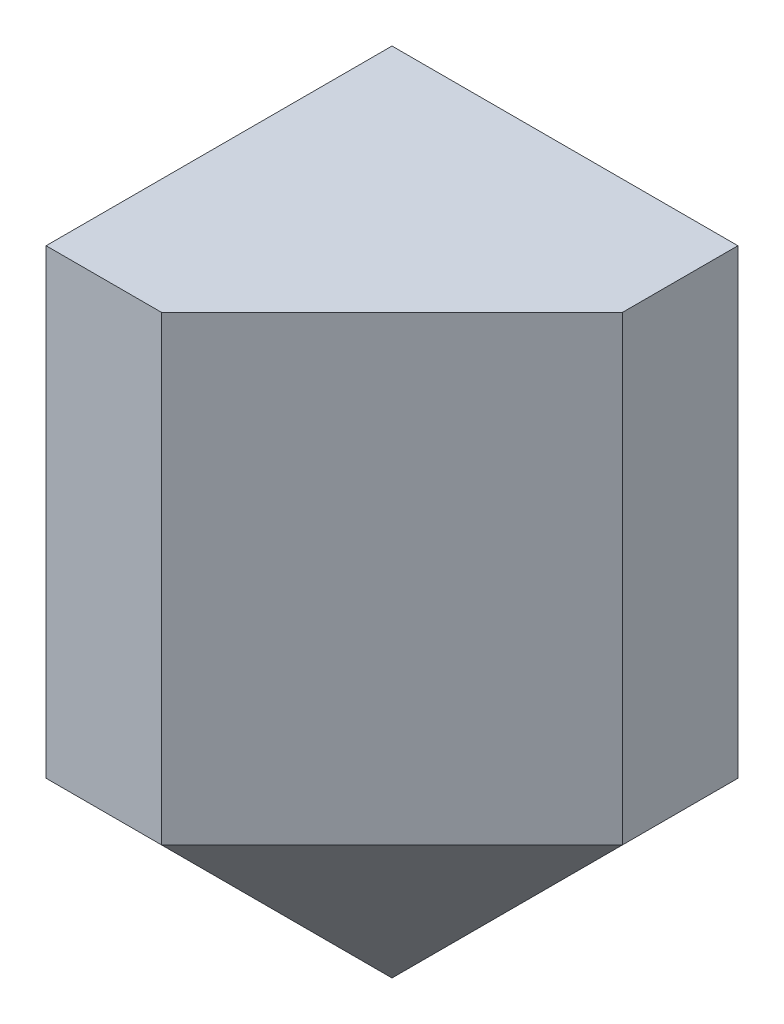
SolidWorks part; units mm, degrees
material "ABS generico"
ref_plane "Piano frontale" through (0, 0, 0) normal (0, 0, 1) x (1, 0, 0)
ref_plane "Piano superiore" through (0, 0, 0) normal (0, 1, 0) x (1, 0, 0)
ref_plane "Piano destro" through (0, 0, 0) normal (1, 0, 0) x (0, 0, -1)
sketch "Schizzo1" plane through (0, 0, 0) normal (0, 0, 1) x (1, 0, 0)
  line L1 (0, 0) -> (30, 0)
  line L2 (0, 0) -> (0, 40)
  line L3 (0, 40) -> (30, 40)
  line L4 (30, 0) -> (30, 40)
  dimension "D1" = 30
  dimension "D2" = 40
extrude "Estrusione-Estrusione1" add sketch "Schizzo1" along normal blind 30
chamfer "Smusso1" distance 20 angle 45 3 edges at (30, 20, 30) (30, 0, 15) (15, 0, 30)
sketch "Schizzo2" plane through (0, 40, 0) normal (0, 1, 0) x (1, 0, 0)
  line L0 (0, 0) -> (30, 0)
  line L1 (30, 0) -> (30, -10)
  line L2 (30, -10) -> (10, -30)
  line L3 (10, -30) -> (0, -30)
  line L4 (0, -30) -> (0, 0)
extrude "Estrusione-Estrusione2" add sketch "Schizzo2" along normal blind 20
hole_wizard "Foro per Vite M5-1" positions "Schizzo3" profile "Schizzo4" hole size "M5" standard "ISO"
sketch "Schizzo3" plane through (0, 0, 0) normal (-1, 0, 0) x (0, 0, 1)
  line L0 (18, 20) -> (18, 34) construction
  line L2 (0, 60) -> (0, 0) construction
  line L4 (18, 48) -> (18, 34) construction
  line L5 (0, 60) -> (30, 60) construction
  point P0 (18, 20)
  point P28 (18, 48)
  point P33 (0, 0)
  dimension "D1" = 18
  dimension "D2" = 12
  dimension "D3" = 14
  dimension "D4" = 14
sketch "Schizzo4" plane through (0, 20, 18) normal (0, 1, 0) x (0, 0, 1)
  line L0 (0, 0) -> (0, 16.6524)
  line L1 (0, 16.6524) -> (2.75, 15)
  line L2 (2.75, 15) -> (2.75, 0)
  line L5 (2.75, 0) -> (0, 0)
  line L10 (0, 16.6524) -> (-2.75, 15) construction
  line L11 (0, -6.35) -> (0, 107.95) construction
  dimension "Hole Dia." = 5.5
  dimension "Hole Depth" = 15
  dimension "Drill Angle" = 118
hole_wizard "Foro per Vite M5-2" positions "Schizzo3D1" profile "Schizzo5" hole size "M5" standard "ISO"
sketch3d "Schizzo3D1"
  line L0 (18, 20, 0) -> (18, 34, 0) construction
  line L2 (0, 60, 0) -> (0, 0, 0) construction
  line L4 (18, 48, 0) -> (18, 34, 0) construction
  line L5 (30, 60, 0) -> (0, 60, 0) construction
  point P2 (18, 20, 0)
  point P21 (18, 48, 0)
  point P26 (0, 0, 0)
  dimension "D1" = 18
  dimension "D2" = 14
  dimension "D3" = 12
  dimension "D4" = 14
sketch "Schizzo5" plane through (18, 20, 0) normal (1, 0, 0) x (0, 1, 0)
  line L0 (0, 0) -> (0, 16.6524)
  line L1 (0, 16.6524) -> (2.75, 15)
  line L2 (2.75, 15) -> (2.75, 0)
  line L5 (2.75, 0) -> (0, 0)
  line L10 (0, 16.6524) -> (-2.75, 15) construction
  line L11 (0, -6.35) -> (0, 107.95) construction
  dimension "Hole Dia." = 5.5
  dimension "Hole Depth" = 15
  dimension "Drill Angle" = 118
